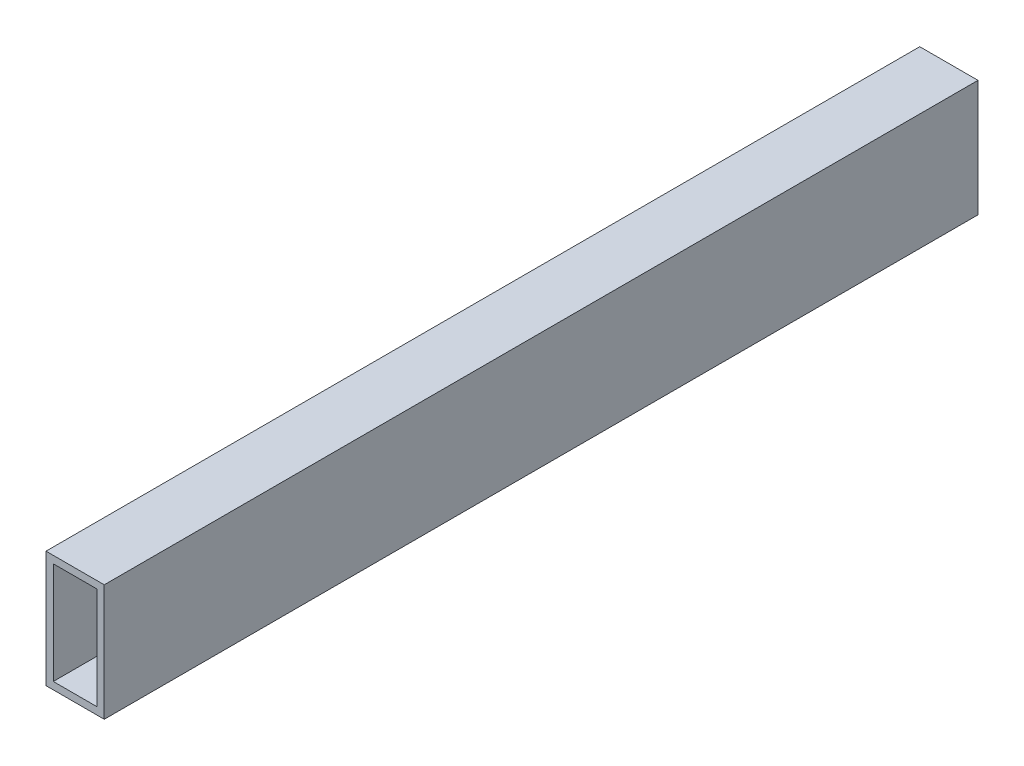
SolidWorks part; units mm, degrees
ref_plane "Front Plane" through (0, 0, 0) normal (0, 0, 1) x (1, 0, 0)
ref_plane "Top Plane" through (0, 0, 0) normal (0, 1, 0) x (1, 0, 0)
ref_plane "Right Plane" through (0, 0, 0) normal (1, 0, 0) x (0, 0, -1)
sketch "Sketch2" plane through (0, 0, 0) normal (0, 0, 1) x (1, 0, 0)
  line L1 (-12.7, -25.4) -> (12.7, -25.4)
  line L2 (-12.7, -25.4) -> (-12.7, 25.4)
  line L3 (-12.7, 25.4) -> (12.7, 25.4)
  line L4 (12.7, -25.4) -> (12.7, 25.4)
  line L5 (-12.7, -25.4) -> (12.7, 25.4) construction
  line L6 (-12.7, 25.4) -> (12.7, -25.4) construction
  line L7 (-9.525, -22.225) -> (9.525, -22.225)
  line L8 (-9.525, -22.225) -> (-9.525, 22.225)
  line L9 (-9.525, 22.225) -> (9.525, 22.225)
  line L10 (9.525, -22.225) -> (9.525, 22.225)
  line L11 (-9.525, -22.225) -> (9.525, 22.225) construction
  line L12 (-9.525, 22.225) -> (9.525, -22.225) construction
  point P0 (0, 0)
  point P6 (0, 0)
  dimension "D1" = 3.175
  dimension "D2" = 3.175
  dimension "D3" = 50.8
  dimension "D4" = 25.4
extrude "Boss-Extrude1" add sketch "Sketch2" along normal mid plane 381
